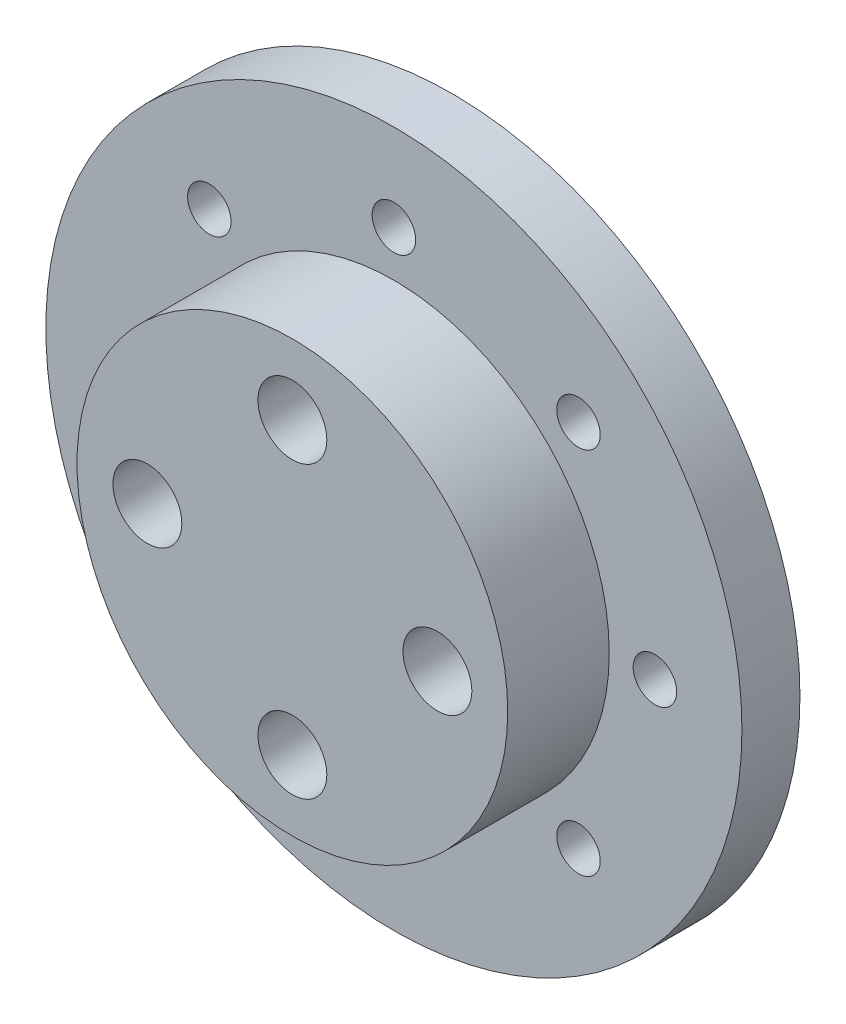
SolidWorks part; units mm, degrees
ref_plane "Plan de face" through (0, 0, 0) normal (0, 0, 1) x (1, 0, 0)
ref_plane "Plan de dessus" through (0, 0, 0) normal (0, 1, 0) x (1, 0, 0)
ref_plane "Plan de droite" through (0, 0, 0) normal (1, 0, 0) x (0, 0, -1)
sketch "Esquisse1" plane through (0, 0, 0) normal (0, 0, 1) x (1, 0, 0)
  circle A0 centre (0, 0) radius 24
  circle A1 centre (0, 18) radius 1.5
  circle A2 centre (12.7279, 12.7279) radius 1.5
  circle A3 centre (18, 0) radius 1.5
  circle A4 centre (12.7279, -12.7279) radius 1.5
  circle A5 centre (0, -18) radius 1.5
  circle A6 centre (-12.7279, -12.7279) radius 1.5
  circle A7 centre (-18, 0) radius 1.5
  circle A8 centre (-12.7279, 12.7279) radius 1.5
  circle A9 centre (0, 0) radius 3
  point P22 (0, 0)
  dimension "D1" = 3
  dimension "D3" = 48
  dimension "D5" = 6
  dimension "D2" = 18
  dimension "D4" = 8
extrude "Boss.-Extru.1" add sketch "Esquisse1" along normal blind 4
sketch "Esquisse2" plane through (0, 0, 4) normal (0, 0, 1) x (1, 0, 0)
  circle A0 centre (0, 0) radius 14.85
  dimension "D1" = 29.7
extrude "Boss.-Extru.2" add sketch "Esquisse2" along normal blind 7 contours A0
sketch "Esquisse3" plane through (0, 0, 11) normal (0, 0, 1) x (1, 0, 0)
  circle A0 centre (0, 10) radius 2.375
  circle A1 centre (10, 0) radius 2.375
  circle A2 centre (0, -10) radius 2.375
  circle A3 centre (-10, 0) radius 2.375
  dimension "D1" = 4.75
  dimension "D2" = 4.75
  dimension "D3" = 4.75
  dimension "D4" = 4.75
  dimension "D5" = 10
  dimension "D6" = 10
  dimension "D7" = 10
  dimension "D8" = 10
extrude "Enlèv. mat.-Extru.1" cut sketch "Esquisse3" against normal blind 10
